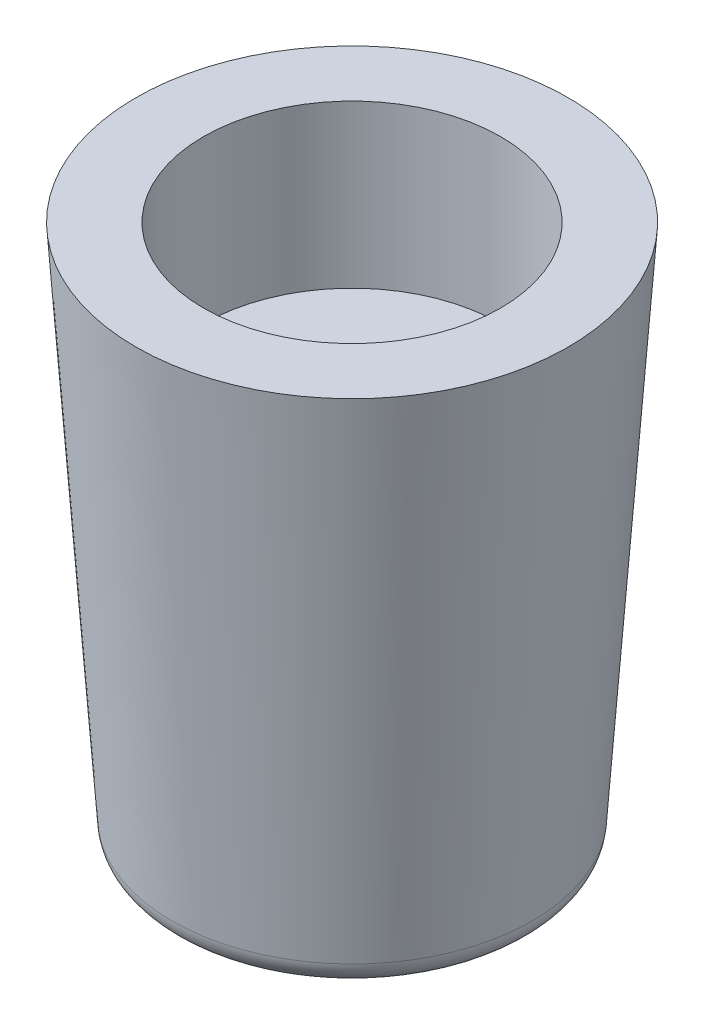
SolidWorks part; units mm, degrees
ref_plane "Front Plane" through (0, 0, 0) normal (0, 0, 1) x (1, 0, 0)
ref_plane "Top Plane" through (0, 0, 0) normal (0, 1, 0) x (1, 0, 0)
ref_plane "Right Plane" through (0, 0, 0) normal (1, 0, 0) x (0, 0, -1)
sketch "Sketch1" plane through (0, 0, 0) normal (0, 1, 0) x (1, 0, 0)
  circle A0 centre (0, 0) radius 4
  dimension "D1" = 8
extrude "Boss-Extrude1" add sketch "Sketch1" against normal blind 10 draft 4
sketch "Sketch2" plane through (0, 0, 0) normal (0, 1, 0) x (1, 0, 0)
  circle A0 centre (0, 0) radius 2.75
  dimension "D1" = 5.5
extrude "Cut-Extrude1" cut sketch "Sketch2" against normal blind 3
fillet "Fillet1" radius 0.5 1 edges at (0, -10, 3.3007)
